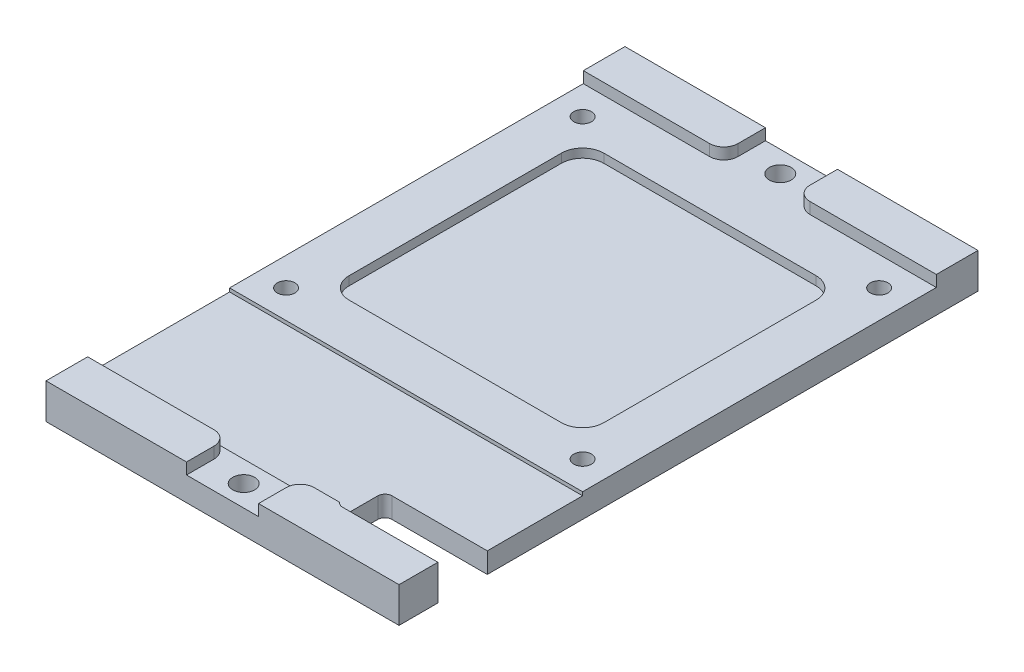
SolidWorks part; units mm, degrees
ref_plane "Спереди" through (0, 0, 0) normal (0, 0, 1) x (1, 0, 0)
ref_plane "Сверху" through (0, 0, 0) normal (0, 1, 0) x (1, 0, 0)
ref_plane "Справа" through (0, 0, 0) normal (1, 0, 0) x (0, 0, -1)
sketch "Основание" plane through (0, 0, 0) normal (0, 1, 0) x (1, 0, 0)
  line L1 (-25, -51) -> (25, -51)
  line L2 (-25, -51) -> (-25, 31)
  line L3 (-25, 31) -> (25, 31)
  line L4 (25, -51) -> (25, 31)
  dimension "D1" = 50
  dimension "D2" = 82
  dimension "D3" = 31
  dimension "D4" = 25
extrude "Бобышка-Вытянуть1" add sketch "Основание" along normal blind 3.4
sketch "Эскиз2" plane through (0, 3.4, 0) normal (0, 1, 0) x (1, 0, 0)
  line L5 (-18.035, -18.035) -> (18.035, -18.035)
  line L6 (-18.035, -18.035) -> (-18.035, 18.035)
  line L7 (-18.035, 18.035) -> (18.035, 18.035)
  line L8 (18.035, -18.035) -> (18.035, 18.035)
  line L9 (-18.035, -18.035) -> (18.035, 18.035) construction
  line L10 (-18.035, 18.035) -> (18.035, -18.035) construction
  point P4 (0, 0)
  dimension "D1" = 36.07
extrude "Выемка для ADR1399KEZ" cut sketch "Эскиз2" against normal blind 1.25
sketch "Эскиз3" plane through (0, 0, 0) normal (0, 1, 0) x (1, 0, 0)
  line L0 (0, 0) -> (33.2111, 0) construction
  line L1 (0, 10.0667) -> (0, -12.5959) construction
  circle A0 centre (-21, 21) radius 1.25
  circle A1 centre (21, 21) radius 1.25
  circle A2 centre (-21, -21) radius 1.25
  circle A3 centre (21, -21) radius 1.25
  circle A4 centre (0, 28) radius 1.55
  circle A5 centre (0, -48) radius 1.55
  dimension "D1" = 2.5
  dimension "D6" = 3.1
  dimension "D7" = 3.1
  dimension "D2" = 21
  dimension "D3" = 21
  dimension "D4" = 28
  dimension "D5" = 48
extrude "Крепежныые винты и внешние вырезы" cut sketch "Эскиз3" along direction (0, -1, 0) on the side of the normal through all from surface at 0 starting at face at (0, 0, 10)
sketch "Эскиз5" plane through (0, 3.4, 0) normal (0, 1, 0) x (1, 0, 0)
  line L0 (25, -51) -> (25, 31) construction
  line L1 (-25, -45) -> (25, -45)
  line L2 (-25, -45) -> (-25, -25)
  line L3 (-25, -25) -> (25, -25)
  line L4 (25, -45) -> (25, -25)
  line L6 (-25, -51) -> (25, -51) construction
  line L9 (-25, 31) -> (-25, -51) construction
  dimension "D1" = 25
  dimension "D2" = 6
extrude "Выемка под компоненты" cut sketch "Эскиз5" against normal blind 0.5
fillet "Скругление под фрезу" radius 3 4 edges at (18.035, 2.775, 18.035) (-18.035, 2.775, 18.035) (-18.035, 2.775, -18.035) (18.035, 2.775, -18.035)
sketch "Эскиз9" plane through (0, 3.4, 0) normal (0, 1, 0) x (1, 0, 0)
  line L1 (-25, 31) -> (-5.1, 31)
  line L2 (-25, 31) -> (-25, 25.1)
  line L3 (-25, 25.1) -> (-5.1, 25.1)
  line L4 (-5.1, 31) -> (-5.1, 25.1)
  line L5 (25, 31) -> (5.1, 31)
  line L6 (25, 31) -> (25, 25.1)
  line L7 (25, 25.1) -> (5.1, 25.1)
  line L8 (5.1, 31) -> (5.1, 25.1)
  line L9 (-25, -51) -> (-5.1, -51)
  line L10 (-25, -51) -> (-25, -45.1)
  line L11 (-25, -45.1) -> (-5.1, -45.1)
  line L12 (-5.1, -51) -> (-5.1, -45.1)
  line L13 (25, -51) -> (5.1, -51)
  line L14 (25, -51) -> (25, -45.1)
  line L15 (25, -45.1) -> (5.1, -45.1)
  line L16 (5.1, -51) -> (5.1, -45.1)
  dimension "D1" = 5.9
  dimension "D2" = 19.9
extrude "Бобышка-Вытянуть2" add sketch "Эскиз9" along normal blind 1.6
sketch "Эскиз7" plane through (0, 0, 0) normal (0, -1, 0) x (1, 0, 0)
  line L1 (-25, 51) -> (25, 51) construction
  line L12 (10.5, 38.5) -> (25, 38.5)
  line L13 (10.5, 38.5) -> (10.5, 45.5)
  line L14 (10.5, 45.5) -> (25, 45.5)
  line L15 (25, 38.5) -> (25, 45.5)
  line L16 (25, 51) -> (25, -31) construction
  dimension "D5" = 5.5
  dimension "D6" = 7
  dimension "D7" = 14.5
extrude "Вырез-Вытянуть7" cut sketch "Эскиз7" against normal through all
fillet "Скругление3" radius 1 2 edges at (10.5, 1.45, 38.5) (10.5, 2.5, 45.5)
fillet "Скругление4" radius 2 4 edges at (5.1, 4.2, 45.1) (-5.1, 4.2, 45.1) (5.1, 4.2, -25.1) (-5.1, 4.2, -25.1)
